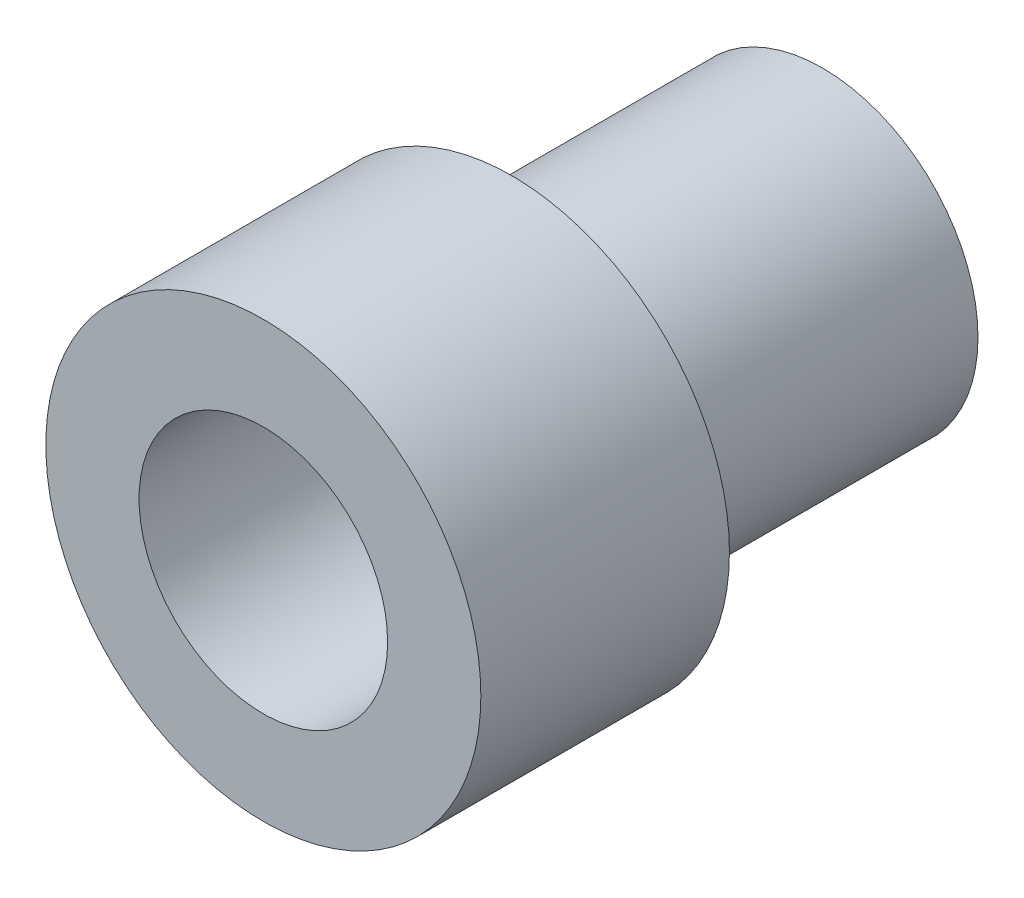
SolidWorks part; units mm, degrees
ref_plane "Front" through (0, 0, 0) normal (0, 0, 1) x (1, 0, 0)
ref_plane "Top" through (0, 0, 0) normal (0, 1, 0) x (1, 0, 0)
ref_plane "Right" through (0, 0, 0) normal (1, 0, 0) x (0, 0, -1)
sketch "Sketch1" plane through (0, 0, 0) normal (0, 0, 1) x (1, 0, 0)
  circle A0 centre (0, 0) radius 1.5
  circle A1 centre (0, 0) radius 2.5
  dimension "D1" = 3
  dimension "D2" = 5
extrude "Extrude1" add sketch "Sketch1" along normal blind 5
sketch "Sketch2" plane through (0, 0, 5) normal (0, 0, 1) x (1, 0, 0)
  circle A0 centre (0, 0) radius 2
  circle A1 centre (0, 0) radius 3.5
  dimension "D1" = 4
  dimension "D2" = 7
extrude "Extrude2" add sketch "Sketch2" along normal blind 4
